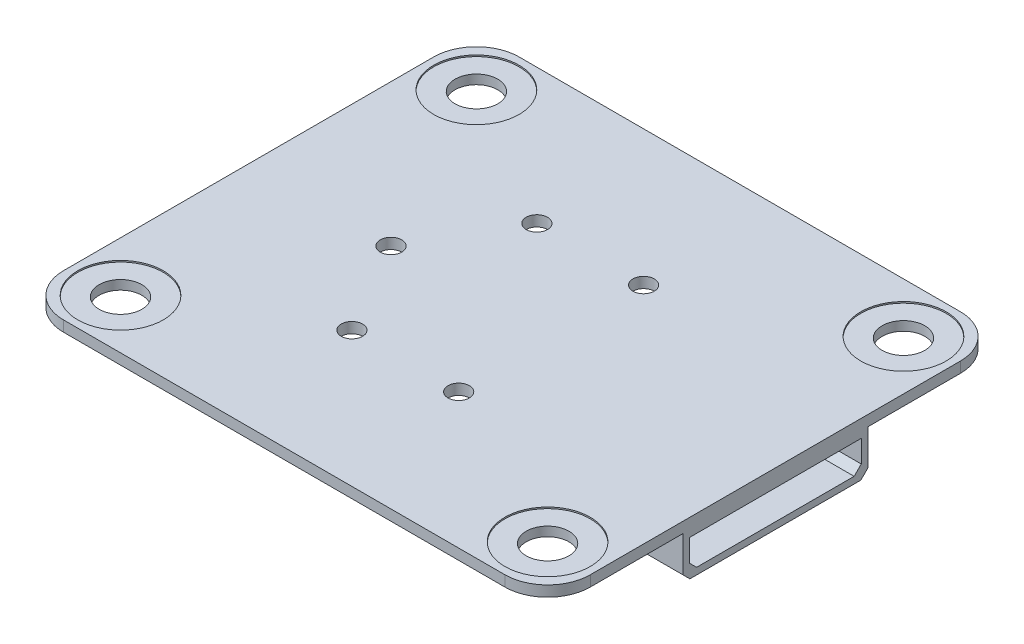
SolidWorks part; units mm, degrees
ref_plane "Front Plane" through (0, 0, 0) normal (0, 0, 1) x (1, 0, 0)
ref_plane "Top Plane" through (0, 0, 0) normal (0, 1, 0) x (1, 0, 0)
ref_plane "Right Plane" through (0, 0, 0) normal (1, 0, 0) x (0, 0, -1)
sketch "Sketch1" plane through (0, 0, 0) normal (0, 1, 0) x (1, 0, 0)
  line L1 (-15.5, 16) -> (15.5, 16)
  line L2 (-18.5, 13) -> (-18.5, -13)
  line L3 (-15.5, -16) -> (15.5, -16)
  line L4 (18.5, 13) -> (18.5, -13)
  line L5 (-18.5, 16) -> (18.5, -16) construction
  line L6 (-18.5, -16) -> (18.5, 16) construction
  arc A0 (15.5, -16) -> (18.5, -13) centre (15.5, -13) ccw
  arc A1 (-18.5, -13) -> (-15.5, -16) centre (-15.5, -13) ccw
  arc A2 (15.5, 16) -> (18.5, 13) centre (15.5, 13) cw
  arc A3 (-15.5, 16) -> (-18.5, 13) centre (-15.5, 13) ccw
  point P0 (0, 0)
  dimension "D1" = 3
extrude "Boss-Extrude1" add sketch "Sketch1" along normal blind 0.75
sketch "Sketch2" plane through (0, 0.75, 0) normal (0, 1, 0) x (1, 0, 0)
  line L0 (0, 12.5) -> (0, 8.4801)
  line L1 (-15, 0) -> (-11.201, 0)
  line L6 (-15, 12.5) -> (15, 12.5)
  line L8 (-15, 12.5) -> (-15, -12.5)
  line L10 (-15, -12.5) -> (15, -12.5)
  line L11 (15, 12.5) -> (15, -12.5)
  circle A0 centre (-15, 12.5) radius 1.5
  circle A1 centre (-15, 12.5) radius 3
  circle A2 centre (15, 12.5) radius 3
  circle A3 centre (15, 12.5) radius 1.5
  circle A4 centre (15, -12.5) radius 3
  circle A5 centre (15, -12.5) radius 1.5
  circle A6 centre (-15, -12.5) radius 3
  circle A7 centre (-15, -12.5) radius 1.5
extrude "Cut-Extrude3" cut sketch "Sketch2" against normal blind 0.1 contours L6 A1 L8 A0 | L8 A1 L6 A0 | L6 A3 L11 A2 | L11 A3 L6 A2 | A5 L11 A4 L10 | A5 L10 A4 L11 | L10 A7 L8 A6 | L8 A7 L10 A6
sketch "Sketch3" plane through (0, 0.75, 0) normal (0, 1, 0) x (1, 0, 0)
  circle A0 centre (-15, 12.5) radius 1.5
  circle A1 centre (15, 12.5) radius 1.5
  circle A2 centre (-15, -12.5) radius 1.5
  circle A3 centre (15, -12.5) radius 1.5
extrude "Cut-Extrude4" cut sketch "Sketch3" against normal blind 3.1
sketch "Sketch4" plane through (0, 0.75, 0) normal (0, 1, 0) x (1, 0, 0)
  line L2 (18.5, 0) -> (-1, 0)
  line L3 (18.5, -13) -> (18.5, 13) construction
  circle A10 centre (-8.5, 0) radius 0.75
  circle A11 centre (2.75, 6.4952) radius 0.75
  circle A12 centre (-4.75, -6.4952) radius 0.75
  circle A13 centre (2.75, -6.4952) radius 0.75
  circle A14 centre (-4.75, 6.4952) radius 0.75
extrude "Cut-Extrude5" cut sketch "Sketch4" against normal blind 10 contours A13 | A12 | A10 | A14 | A11
sketch "Sketch6" plane through (0, 0, 0) normal (0, -1, 0) x (1, 0, 0)
  line L0 (18.5, 13) -> (18.5, -13) construction
  line L1 (18.5, -6.5037) -> (12.1592, -6.5037)
  line L3 (18.5, 6.5037) -> (12.1592, 6.5037)
  line L4 (12.1592, -6.5037) -> (12.1592, 6.5037)
  line L7 (18.5, -6.5037) -> (18.5, 6.5037)
  point P0 (18.5, 0)
extrude "Boss-Extrude2" add sketch "Sketch6" along normal blind 3
sketch "Sketch7" plane through (18.5, 0, 0) normal (1, 0, 0) x (0, 0, -1)
  line L0 (0, -3) -> (0, -2.5305)
  line L1 (6.5037, -3) -> (-6.5037, -3) construction
  line L2 (0, -0.4695) -> (0, 0)
  line L3 (6.0341, -2.5305) -> (-6.0341, -2.5305)
  line L4 (6.0341, -2.5305) -> (6.0341, -0.4695)
  line L5 (6.0341, -0.4695) -> (-6.0341, -0.4695)
  line L6 (-6.0341, -2.5305) -> (-6.0341, -0.4695)
  point P5 (0, -1.5)
extrude "Cut-Extrude6" cut sketch "Sketch7" against normal blind 5 contours L6 L3 L4 L5
chamfer "Chamfer2" distance 0.5 4 edges at (15.3296, -3, -6.5037) (15.3296, -3, 6.5037) (16, -2.5305, 6.0341) (16, -2.5305, -6.0341)
